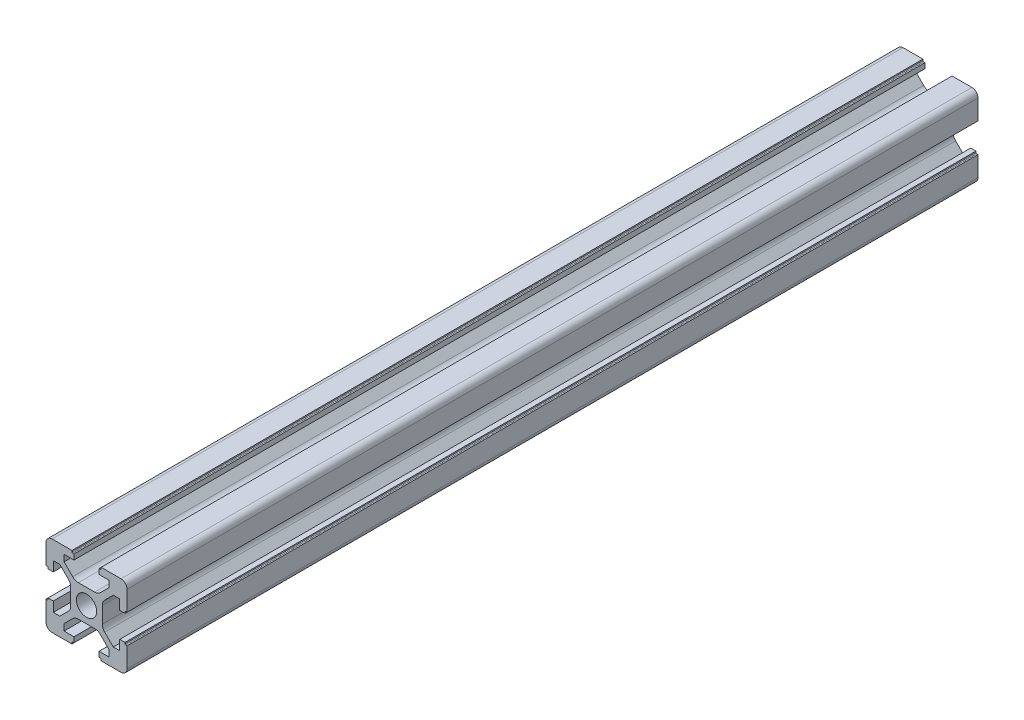
SolidWorks part; units mm, degrees
ref_plane "Спереди" through (0, 0, 0) normal (0, 0, 1) x (1, 0, 0)
ref_plane "Сверху" through (0, 0, 0) normal (0, 1, 0) x (1, 0, 0)
ref_plane "Справа" through (0, 0, 0) normal (1, 0, 0) x (0, 0, -1)
sketch "Sketch1" plane through (0, 0, 0) normal (0, 0, 1) x (1, 0, 0)
  line L0 (0, 10) -> (0, -10) construction
  line L1 (-10, -10) -> (10, -10) construction
  line L2 (-10, -10) -> (-10, 10) construction
  line L3 (-10, 10) -> (10, 10) construction
  line L4 (10, -10) -> (10, 10) construction
  line L5 (-10, -10) -> (10, 10) construction
  line L6 (-10, 10) -> (10, -10) construction
  line L7 (-10, 0) -> (10, 0) construction
  line L8 (0, 3.9) -> (-2.0109, 3.9)
  line L9 (-3.4251, 4.4858) -> (-5.5393, 6.6)
  line L10 (-5.5393, 6.6) -> (-5.5393, 8.2)
  line L11 (-5.5393, 8.2) -> (-3.1, 8.2)
  line L12 (-3.1, 8.2) -> (-3.1, 9.5)
  line L13 (-3.1, 9.5) -> (-3.4, 9.5)
  line L14 (-3.6, 9.7) -> (-3.6, 10)
  line L15 (-3.6, 10) -> (-8.5, 10)
  line L16 (-10, 3.6) -> (-10, 8.5)
  line L17 (-9.7, 3.6) -> (-10, 3.6)
  line L18 (-9.5, 3.1) -> (-9.5, 3.4)
  line L19 (-8.2, 3.1) -> (-9.5, 3.1)
  line L20 (-8.2, 5.5393) -> (-8.2, 3.1)
  line L21 (-6.6, 5.5393) -> (-8.2, 5.5393)
  line L22 (-4.4858, 3.4251) -> (-6.6, 5.5393)
  line L23 (-3.9, 0) -> (-3.9, 2.0109)
  line L24 (3.9, 0) -> (3.9, 2.0109)
  line L25 (4.4858, 3.4251) -> (6.6, 5.5393)
  line L26 (6.6, 5.5393) -> (8.2, 5.5393)
  line L27 (8.2, 5.5393) -> (8.2, 3.1)
  line L28 (8.2, 3.1) -> (9.5, 3.1)
  line L29 (9.5, 3.1) -> (9.5, 3.4)
  line L30 (9.7, 3.6) -> (10, 3.6)
  line L31 (10, 3.6) -> (10, 8.5)
  line L32 (3.6, 10) -> (8.5, 10)
  line L33 (3.6, 9.7) -> (3.6, 10)
  line L34 (3.1, 9.5) -> (3.4, 9.5)
  line L35 (3.1, 8.2) -> (3.1, 9.5)
  line L36 (5.5393, 8.2) -> (3.1, 8.2)
  line L37 (5.5393, 6.6) -> (5.5393, 8.2)
  line L38 (3.4251, 4.4858) -> (5.5393, 6.6)
  line L39 (0, 3.9) -> (2.0109, 3.9)
  line L40 (0, -3.9) -> (2.0109, -3.9)
  line L41 (3.4251, -4.4858) -> (5.5393, -6.6)
  line L42 (5.5393, -6.6) -> (5.5393, -8.2)
  line L43 (5.5393, -8.2) -> (3.1, -8.2)
  line L44 (3.1, -8.2) -> (3.1, -9.5)
  line L45 (3.1, -9.5) -> (3.4, -9.5)
  line L46 (3.6, -9.7) -> (3.6, -10)
  line L47 (3.6, -10) -> (8.5, -10)
  line L48 (10, -3.6) -> (10, -8.5)
  line L49 (9.7, -3.6) -> (10, -3.6)
  line L50 (9.5, -3.1) -> (9.5, -3.4)
  line L51 (8.2, -3.1) -> (9.5, -3.1)
  line L52 (8.2, -5.5393) -> (8.2, -3.1)
  line L53 (6.6, -5.5393) -> (8.2, -5.5393)
  line L54 (4.4858, -3.4251) -> (6.6, -5.5393)
  line L55 (3.9, 0) -> (3.9, -2.0109)
  line L56 (-3.9, 0) -> (-3.9, -2.0109)
  line L57 (-4.4858, -3.4251) -> (-6.6, -5.5393)
  line L58 (-6.6, -5.5393) -> (-8.2, -5.5393)
  line L59 (-8.2, -5.5393) -> (-8.2, -3.1)
  line L60 (-8.2, -3.1) -> (-9.5, -3.1)
  line L61 (-9.5, -3.1) -> (-9.5, -3.4)
  line L62 (-9.7, -3.6) -> (-10, -3.6)
  line L63 (-10, -3.6) -> (-10, -8.5)
  line L64 (-3.6, -10) -> (-8.5, -10)
  line L65 (-3.6, -9.7) -> (-3.6, -10)
  line L66 (-3.1, -9.5) -> (-3.4, -9.5)
  line L67 (-3.1, -8.2) -> (-3.1, -9.5)
  line L68 (-5.5393, -8.2) -> (-3.1, -8.2)
  line L69 (-5.5393, -6.6) -> (-5.5393, -8.2)
  line L70 (-3.4251, -4.4858) -> (-5.5393, -6.6)
  line L71 (0, -3.9) -> (-2.0109, -3.9)
  circle A0 centre (0, 0) radius 2.5
  arc A1 (-8.5, 10) -> (-10, 8.5) centre (-8.5, 8.5) ccw
  arc A2 (-2.0109, 3.9) -> (-3.4251, 4.4858) centre (-2.0109, 5.9) cw
  arc A3 (-3.4, 9.5) -> (-3.6, 9.7) centre (-3.4, 9.7) cw
  arc A4 (-9.5, 3.4) -> (-9.7, 3.6) centre (-9.7, 3.4) ccw
  arc A5 (-3.9, 2.0109) -> (-4.4858, 3.4251) centre (-5.9, 2.0109) ccw
  arc A6 (10, 8.5) -> (8.5, 10) centre (8.5, 8.5) ccw
  arc A7 (3.9, 2.0109) -> (4.4858, 3.4251) centre (5.9, 2.0109) cw
  arc A8 (9.5, 3.4) -> (9.7, 3.6) centre (9.7, 3.4) cw
  arc A9 (3.4, 9.5) -> (3.6, 9.7) centre (3.4, 9.7) ccw
  arc A10 (2.0109, 3.9) -> (3.4251, 4.4858) centre (2.0109, 5.9) ccw
  arc A11 (8.5, -10) -> (10, -8.5) centre (8.5, -8.5) ccw
  arc A12 (2.0109, -3.9) -> (3.4251, -4.4858) centre (2.0109, -5.9) cw
  arc A13 (3.4, -9.5) -> (3.6, -9.7) centre (3.4, -9.7) cw
  arc A14 (9.5, -3.4) -> (9.7, -3.6) centre (9.7, -3.4) ccw
  arc A15 (3.9, -2.0109) -> (4.4858, -3.4251) centre (5.9, -2.0109) ccw
  arc A16 (-10, -8.5) -> (-8.5, -10) centre (-8.5, -8.5) ccw
  arc A17 (-3.9, -2.0109) -> (-4.4858, -3.4251) centre (-5.9, -2.0109) cw
  arc A18 (-9.5, -3.4) -> (-9.7, -3.6) centre (-9.7, -3.4) cw
  arc A19 (-3.4, -9.5) -> (-3.6, -9.7) centre (-3.4, -9.7) ccw
  arc A20 (-2.0109, -3.9) -> (-3.4251, -4.4858) centre (-2.0109, -5.9) ccw
  point P0 (0, 0)
  point P42 (0, 0)
  point P70 (0, 0)
  point P98 (0, 0)
  point P126 (0, 0)
  dimension "D3" = 5
  dimension "D4" = 3
  dimension "D12" = 2
  dimension "D13" = 0.2
  dimension "D1" = 20
  dimension "D2" = 20
  dimension "D5" = 6.2
  dimension "D6" = 7.2
  dimension "D7" = 1.8
  dimension "D8" = 0.5
  dimension "D9" = 3.4
  dimension "D10" = 1.5
  dimension "D11" = 6.1
  dimension "D14" = 4
extrude "Бобышка-Вытянуть1" add sketch "Sketch1" along normal blind 210
